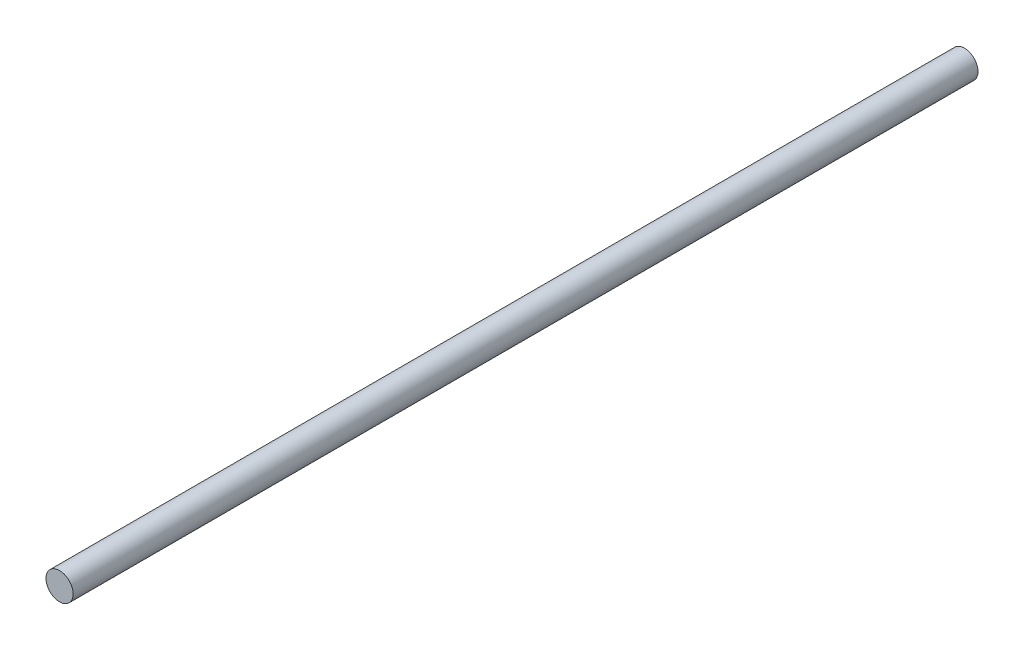
SolidWorks part; units mm, degrees
ref_plane "Front Plane" through (0, 0, 0) normal (0, 0, 1) x (1, 0, 0)
ref_plane "Top Plane" through (0, 0, 0) normal (0, 1, 0) x (1, 0, 0)
ref_plane "Right Plane" through (0, 0, 0) normal (1, 0, 0) x (0, 0, -1)
sketch "Esquisse1" plane through (0, 0, 0) normal (0, 0, 1) x (1, 0, 0)
  circle A0 centre (0, 0) radius 3
  dimension "D1" = 6
extrude "Boss.-Extru.1" add sketch "Esquisse1" along normal blind 200
